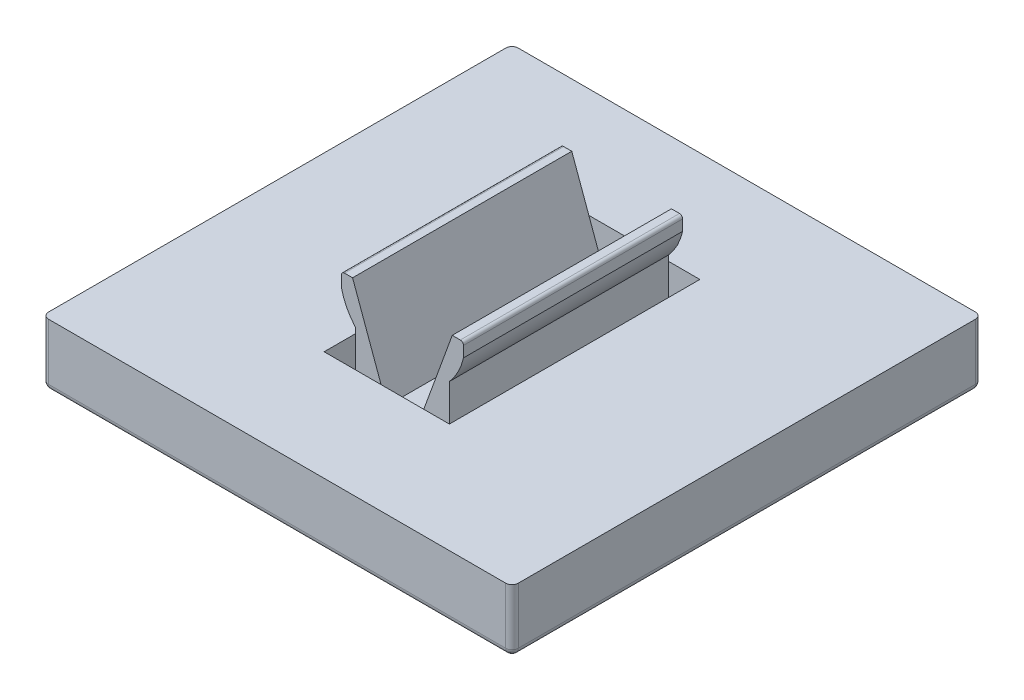
SolidWorks part; units mm, degrees
ref_plane "前视基准面" through (0, 0, 0) normal (0, 0, 1) x (1, 0, 0)
ref_plane "上视基准面" through (0, 0, 0) normal (0, 1, 0) x (1, 0, 0)
ref_plane "右视基准面" through (0, 0, 0) normal (1, 0, 0) x (0, 0, -1)
sketch "草图1" plane through (0, 0, 0) normal (0, 1, 0) x (1, 0, 0)
  line L0 (7.5, 7.5) -> (7.5, -7.5)
  line L1 (7.5, 7.5) -> (-7.5, 7.5)
  line L2 (7.5, -7.5) -> (-7.5, -7.5)
  line L3 (-7.5, 7.5) -> (-7.5, -7.5)
  line L4 (7.5, 7.5) -> (-7.5, -7.5) construction
  line L5 (7.5, -7.5) -> (-7.5, 7.5) construction
  point P1 (0, 0)
  dimension "D1" = 15
  dimension "D2" = 15
extrude "凸台-拉伸1" add sketch "草图1" along normal blind 2
sketch "草图2" plane through (0, 2, 0) normal (0, 1, 0) x (1, 0, 0)
  line L0 (2, 4) -> (2, -4)
  line L1 (2, 4) -> (-2, 4)
  line L2 (2, -4) -> (-2, -4)
  line L3 (-2, 4) -> (-2, -4)
  line L4 (2, 4) -> (-2, -4) construction
  line L5 (2, -4) -> (-2, 4) construction
  point P1 (0, 0)
  dimension "D1" = 4
  dimension "D2" = 8
extrude "切除-拉伸1" cut sketch "草图2" against normal blind 1
sketch "草图3" plane through (0, 0, 0) normal (0, 0, 1) x (1, 0, 0)
  line L0 (0, 0) -> (0, 1) construction
  line L1 (0, 1) -> (0, 4) construction
  line L2 (0, 1) -> (-0.5, 1) construction
  line L3 (-0.5, 1) -> (-1.5, 1)
  line L4 (-1.5, 1) -> (-1.5, 2.6771)
  line L5 (-0.5, 1) -> (-1.5919, 4)
  line L6 (-1.95, 4) -> (-1.95, 3.5556)
  line L7 (-1.5919, 4) -> (-1.95, 4)
  line L8 (1.5919, 4) -> (1.95, 4)
  line L9 (1.95, 4) -> (1.95, 3.5556)
  line L10 (0.5, 1) -> (1.5919, 4)
  line L11 (1.5, 1) -> (1.5, 2.6771)
  line L12 (0.5, 1) -> (1.5, 1)
  arc A0 (-1.95, 3.5556) -> (-1.5, 2.6771) centre (0, 4) ccw
  arc A1 (1.95, 3.5556) -> (1.5, 2.6771) centre (0, 4) cw
  dimension "D5" = 4
  dimension "D1" = 1.5
  dimension "D2" = 1
  dimension "D3" = 3
  dimension "D4" = 1.95
  dimension "D6" = 0.5
  dimension "D7" = 20
extrude "凸台-拉伸2" add sketch "草图3" along normal blind 3.5 and the other way blind 3.5
fillet "圆角1" radius 0.1 2 edges at (1.95, 4, 0) (-1.95, 4, 0)
fillet "圆角2" radius 0.2 8 edges at (-7.5, 0, 0) (0, 0, 7.5) (7.5, 0, 0) (0, 0, -7.5) (-7.5, 1, 7.5) (-7.5, 1, -7.5) (7.5, 1, -7.5) (7.5, 1, 7.5)
